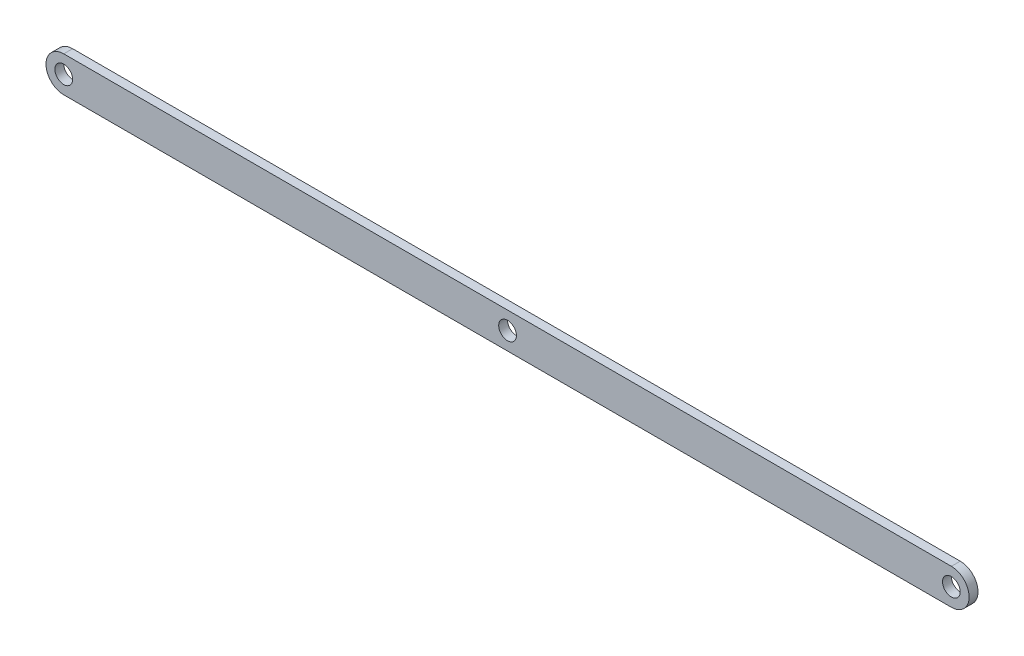
SolidWorks part; units mm, degrees
ref_plane "Front Plane" through (0, 0, 0) normal (0, 0, 1) x (1, 0, 0)
ref_plane "Top Plane" through (0, 0, 0) normal (0, 1, 0) x (1, 0, 0)
ref_plane "Right Plane" through (0, 0, 0) normal (1, 0, 0) x (0, 0, -1)
sketch "Sketch1" plane through (0, 0, 0) normal (0, 0, 1) x (1, 0, 0)
  line L0 (-250, 0) -> (250, 0) construction
  line L3 (-250, 10) -> (250, 10)
  line L4 (-250, -10) -> (250, -10)
  arc A2 (-250, 10) -> (-250, -10) centre (-250, 0) ccw
  arc A3 (250, -10) -> (250, 10) centre (250, 0) ccw
  circle A4 centre (-250, 0) radius 5
  circle A5 centre (0, 0) radius 5
  circle A6 centre (250, 0) radius 5
  point P3 (0, 0)
  dimension "D2" = 10
  dimension "D3" = 10
  dimension "D1" = 500
  dimension "D4" = 3
extrude "Boss-Extrude1" add sketch "Sketch1" along normal blind 5
